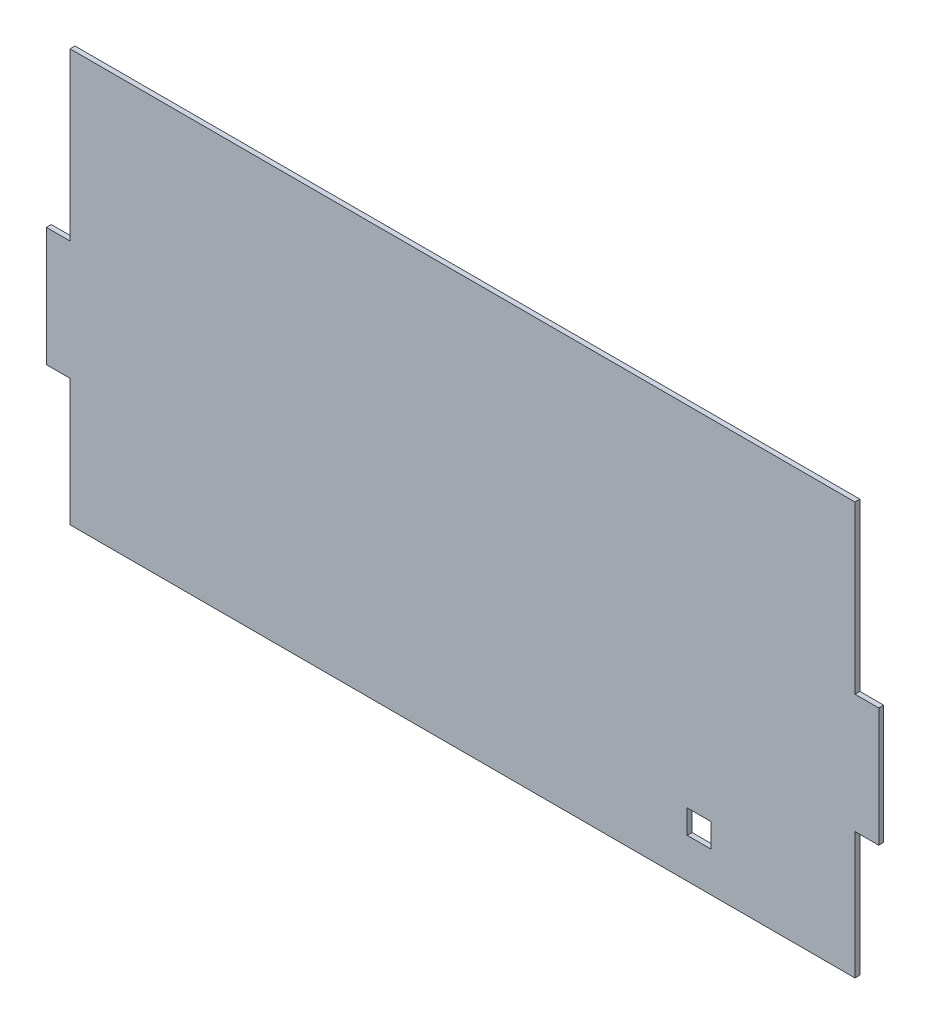
SolidWorks part; units mm, degrees
ref_plane "Front Plane" through (0, 0, 0) normal (0, 0, 1) x (1, 0, 0)
ref_plane "Top Plane" through (0, 0, 0) normal (0, 1, 0) x (1, 0, 0)
ref_plane "Right Plane" through (0, 0, 0) normal (1, 0, 0) x (0, 0, -1)
sketch "Sketch1" plane through (0, 0, 0) normal (0, 0, 1) x (1, 0, 0)
  line L13077 (987.7233, 1158.8359) -> (1002.2432, 1158.8359)
  line L13078 (1002.2432, 1158.8359) -> (1002.2432, 1231.4386)
  line L13079 (1002.2432, 1231.4386) -> (987.7233, 1231.4386)
  line L13080 (987.7233, 1231.4386) -> (987.7233, 1333.0744)
  line L13081 (987.7233, 1333.0744) -> (508.564, 1333.0744)
  line L13082 (508.564, 1333.0744) -> (508.564, 1231.4386)
  line L13083 (508.564, 1231.4386) -> (494.0441, 1231.4386)
  line L13084 (494.0441, 1231.4386) -> (494.0441, 1158.8359)
  line L13085 (494.0441, 1158.8359) -> (508.564, 1158.8359)
  line L13086 (508.564, 1158.8359) -> (508.564, 1081.3977)
  line L13087 (508.564, 1081.3977) -> (987.7233, 1081.3977)
  line L13088 (987.7233, 1081.3977) -> (987.7233, 1158.8359)
  line L13089 (885.3105, 1105.6036) -> (885.3105, 1120.1234)
  line L13090 (885.3105, 1120.1234) -> (899.8304, 1120.1234)
  line L13091 (899.8304, 1120.1234) -> (899.8304, 1105.6036)
  line L13092 (899.8304, 1105.6036) -> (885.3105, 1105.6036)
  dimension "D1" = 101.6358
  dimension "D2" = 479.1593
  dimension "D3" = 14.5199
  dimension "D4" = 72.6027
  dimension "D5" = 251.6768
extrude "Boss-Extrude1" add sketch "Sketch1" along normal blind 3
